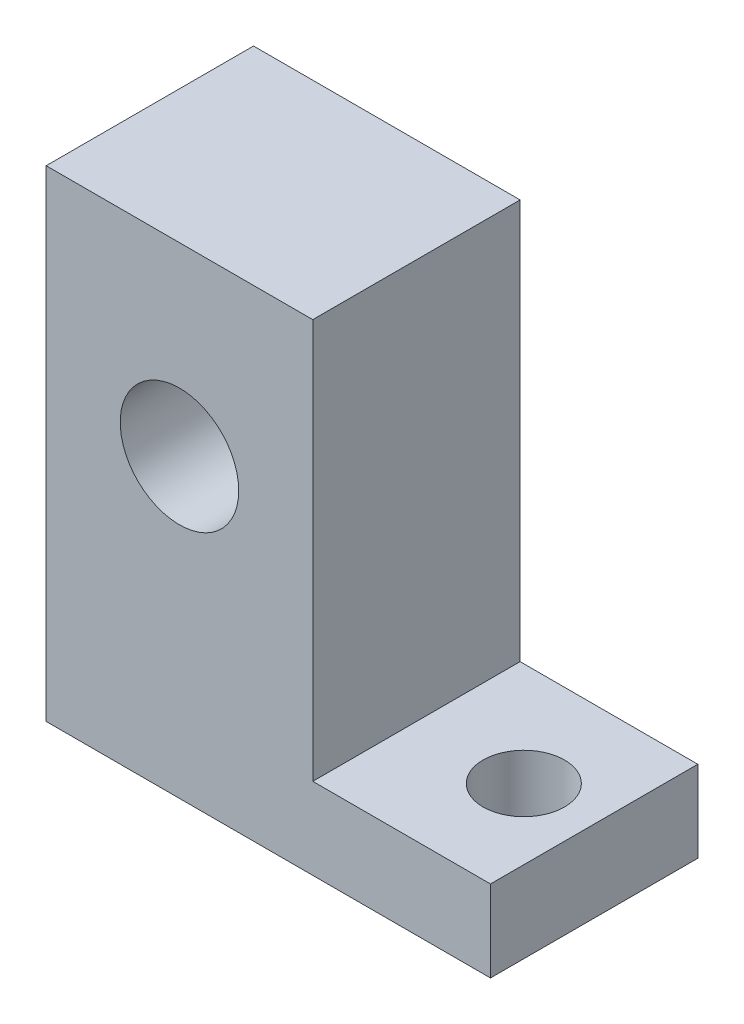
SolidWorks part; units mm, degrees
ref_plane "前视基准面" through (0, 0, 0) normal (0, 0, 1) x (1, 0, 0)
ref_plane "上视基准面" through (0, 0, 0) normal (0, 1, 0) x (1, 0, 0)
ref_plane "右视基准面" through (0, 0, 0) normal (1, 0, 0) x (0, 0, -1)
sketch "草图1" plane through (0, 0, 0) normal (0, 0, 1) x (1, 0, 0)
  line L0 (-21, -10.75) -> (-9, -10.75)
  line L1 (-21, -16.25) -> (21, -16.25)
  line L2 (-21, -16.25) -> (-21, -10.75)
  line L3 (-9, 16.25) -> (9, 16.25)
  line L4 (21, -16.25) -> (21, -10.75)
  line L5 (-21, -16.25) -> (9, 6.9643) construction
  line L6 (-9, 6.9643) -> (21, -16.25) construction
  line L7 (-9, -10.75) -> (-9, 16.25)
  line L8 (0, 16.25) -> (0, -16.25) construction
  line L9 (21, -10.75) -> (9, -10.75)
  line L10 (9, -10.75) -> (9, 16.25)
  circle A0 centre (0, 3.75) radius 4
  point P0 (0, 0)
  dimension "D1" = 8
  dimension "D5" = 20
  dimension "D2" = 42
  dimension "D3" = 5.5
  dimension "D4" = 9
extrude "凸台-拉伸1" add sketch "草图1" along normal blind 14
sketch "草图2" plane through (0, -10.75, 0) normal (0, 1, 0) x (1, 0, 0)
  line L0 (-21, -7) -> (21, -7) construction
  line L1 (-21, -14) -> (-21, 0) construction
  line L2 (21, -14) -> (21, 0) construction
  circle A0 centre (-16.25, -7) radius 2.75
  circle A1 centre (16.25, -7) radius 2.75
  dimension "D1" = 5.5
  dimension "D2" = 5.5
  dimension "D3" = 4.75
  dimension "D4" = 4.75
extrude "切除-拉伸1" cut sketch "草图2" against normal blind 14
sketch "草图3" plane through (0, -10.75, 0) normal (0, 1, 0) x (1, 0, 0)
  line L4 (-9, 0) -> (-21, 0)
  line L5 (-21, 0) -> (-21, -14)
  line L6 (-21, -14) -> (-9, -14)
  line L7 (-9, -14) -> (-9, 0)
  line L8 (-9, 0) -> (-21, 0)
  line L9 (-21, 0) -> (-21, -14)
  line L10 (-21, -14) -> (-9, -14)
  line L11 (-9, -14) -> (-9, 0)
  dimension "D1" = 0
extrude "切除-拉伸2" cut sketch "草图3" against normal blind 10
